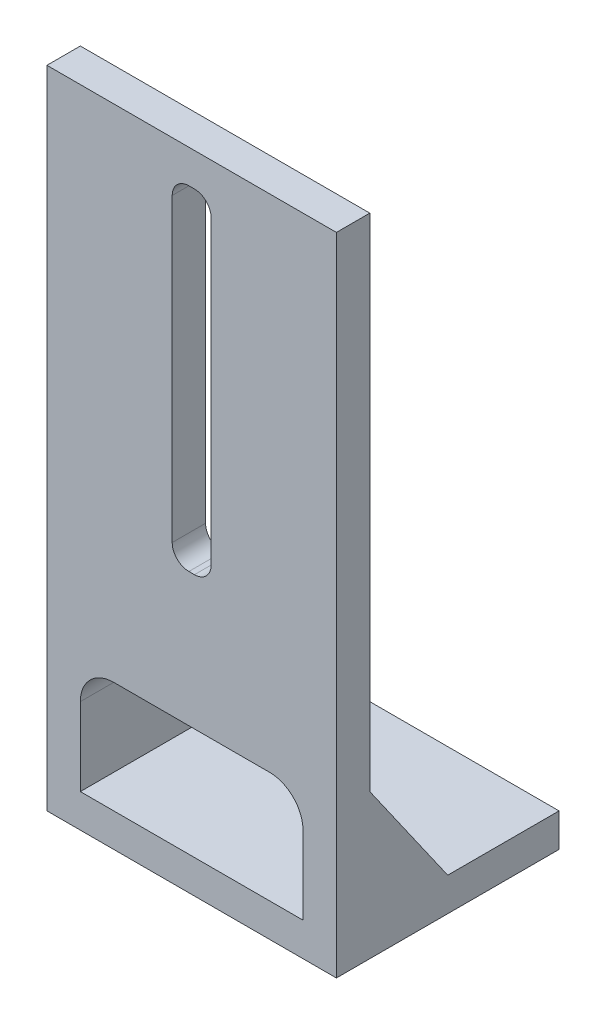
SolidWorks part; units mm, degrees
ref_plane "Front" through (0, 0, 0) normal (0, 0, 1) x (1, 0, 0)
ref_plane "Top" through (0, 0, 0) normal (0, 1, 0) x (1, 0, 0)
ref_plane "Right" through (0, 0, 0) normal (1, 0, 0) x (0, 0, -1)
sketch "Esboço1" plane through (0, 0, 0) normal (0, 1, 0) x (1, 0, 0)
  line L1 (-4.922, 9.0418) -> (21.078, 9.0418)
  line L2 (-4.922, 9.0418) -> (-4.922, -10.9582)
  line L3 (-4.922, -10.9582) -> (21.078, -10.9582)
  line L4 (21.078, 9.0418) -> (21.078, -10.9582)
  dimension "D1" = 26
  dimension "D2" = 20
extrude "Ressalto-extrusão1" add sketch "Esboço1" along normal blind 3
sketch "Esboço2" plane through (0, 3, 0) normal (0, 1, 0) x (1, 0, 0)
  line L0 (-4.922, 9.0418) -> (-4.922, -10.9582) construction
  line L1 (21.078, -10.9582) -> (-4.922, -10.9582)
  line L2 (21.078, -10.9582) -> (21.078, -7.9582)
  line L3 (21.078, -7.9582) -> (-4.922, -7.9582)
  line L4 (-4.922, -10.9582) -> (-4.922, -7.9582)
  dimension "D1" = 3
extrude "Ressalto-extrusão2" add sketch "Esboço2" along normal blind 55
sketch "Esboço3" plane through (0, 3, 0) normal (0, 1, 0) x (1, 0, 0)
  line L0 (21.078, -7.9582) -> (21.078, -0.9582)
  line L1 (-4.922, -7.9582) -> (-1.922, -7.9582)
  line L2 (-4.922, -7.9582) -> (-4.922, -0.9582)
  line L3 (-4.922, -0.9582) -> (-1.922, -0.9582)
  line L4 (-1.922, -7.9582) -> (-1.922, -0.9582)
  line L5 (18.078, -0.9582) -> (21.078, -0.9582)
  line L6 (18.078, -7.9582) -> (18.078, -0.9582)
  line L7 (18.078, -7.9582) -> (21.078, -7.9582)
  dimension "D1" = 3
  dimension "D2" = 7
  dimension "D3" = 2
extrude "Ressalto-extrusão3" add sketch "Esboço3" along normal blind 10
sketch "Esboço4" plane through (-4.922, 0, 0) normal (-1, 0, 0) x (0, 0, 1)
  line L0 (0.9582, 3) -> (7.9582, 13)
  line L1 (7.9582, 13) -> (0.9582, 13)
  line L2 (0.9582, 13) -> (0.9582, 3)
extrude "Corte-extrusão1" cut sketch "Esboço4" against normal through all
sketch "Esboço6" plane through (0, 0, 7.9582) normal (0, 0, -1) x (-1, 0, 0)
  line L1 (-18.078, 3) -> (1.922, 3)
  line L2 (-18.078, 3) -> (-18.078, 13)
  line L3 (-18.078, 13) -> (1.922, 13)
  line L4 (1.922, 3) -> (1.922, 13)
  dimension "D1" = 10
extrude "Corte-extrusão2" cut sketch "Esboço6" against normal up to next
fillet "Filete1" radius 3 2 edges at (-1.922, 13, 9.4582) (18.078, 13, 9.4582)
sketch "Esboço7" plane through (0, 0, 10.9582) normal (0, 0, 1) x (1, 0, 0)
  line L0 (8.078, 58) -> (8.078, 0) construction
  line L1 (-4.922, 58) -> (21.078, 58) construction
  line L2 (-4.922, 0) -> (21.078, 0) construction
  line L3 (8.078, 58) -> (8.078, 55)
  line L4 (9.828, 55) -> (6.328, 55)
  line L5 (6.328, 55) -> (6.328, 25)
  line L6 (6.328, 25) -> (9.828, 25)
  line L7 (9.828, 25) -> (9.828, 55)
  point P10 (8.078, 55)
  dimension "D1" = 3
  dimension "D2" = 3.5
  dimension "D3" = 30
extrude "Corte-extrusão3" cut sketch "Esboço7" against normal up to next contours L0 L4 L5 L6 | L4 L0 L6 L7
fillet "Filete2" radius 1.5 4 edges at (6.328, 25, 9.4582) (9.828, 25, 9.4582) (9.828, 55, 9.4582) (6.328, 55, 9.4582)
